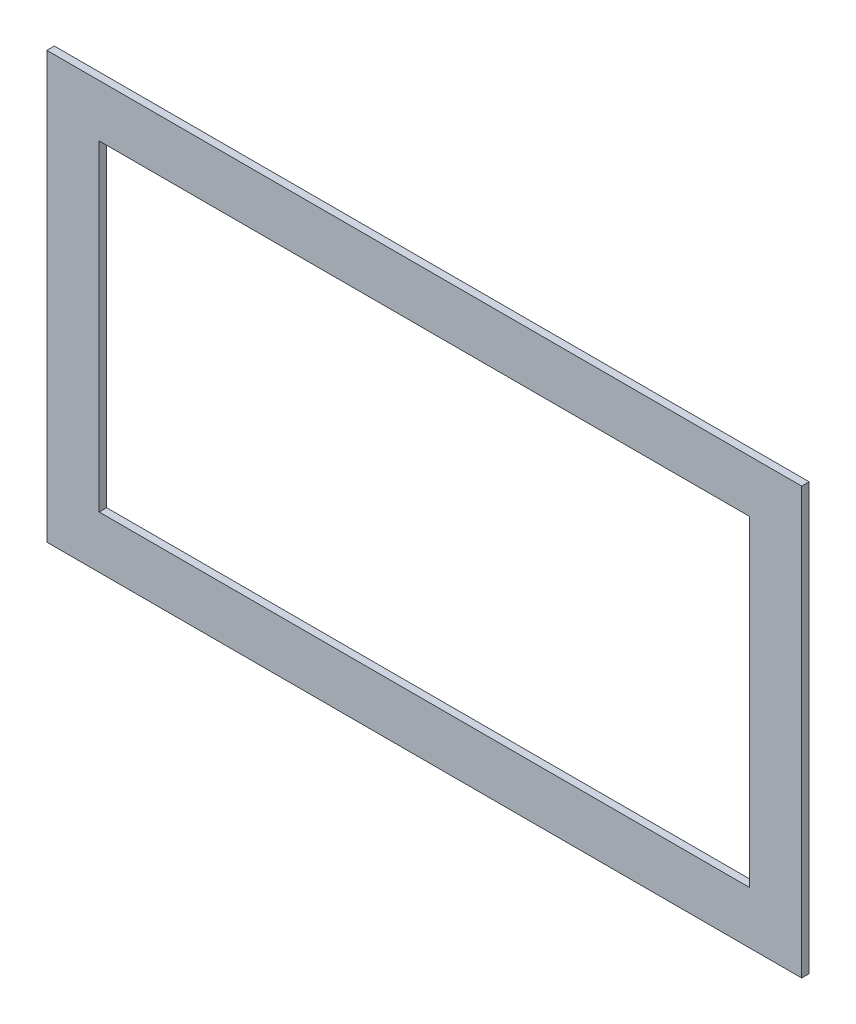
SolidWorks part; units mm, degrees
ref_plane "Front Plane" through (0, 0, 0) normal (0, 0, 1) x (1, 0, 0)
ref_plane "Top Plane" through (0, 0, 0) normal (0, 1, 0) x (1, 0, 0)
ref_plane "Right Plane" through (0, 0, 0) normal (1, 0, 0) x (0, 0, -1)
sketch "Sketch1" plane through (0, 0, 0) normal (0, 0, 1) x (1, 0, 0)
  line L1 (0, 0) -> (101, 0)
  line L2 (0, 0) -> (0, 57)
  line L3 (0, 57) -> (101, 57)
  line L4 (101, 0) -> (101, 57)
  line L5 (7, 7) -> (94, 7)
  line L6 (7, 7) -> (7, 50)
  line L7 (7, 50) -> (94, 50)
  line L8 (94, 7) -> (94, 50)
  dimension "D1" = 7
  dimension "D2" = 94
  dimension "D3" = 101
  dimension "D4" = 7
  dimension "D5" = 50
  dimension "D6" = 57
extrude "Profile" add sketch "Sketch1" along normal blind 1
equation "\"Profile_Depth\"= 1mm"
equation "\"D1@Profile\" = \"Profile_Depth\""
equation "\"Profile_Sketch_1\"= 7mm"
equation "\"D1@Sketch1\" = \"Profile_Sketch_1\""
equation "\"Profile_Sketch_2\"= 94mm"
equation "\"D2@Sketch1\" = \"Profile_Sketch_2\""
equation "\"Profile_Sketch_3\"= 101mm"
equation "\"D3@Sketch1\" = \"Profile_Sketch_3\""
equation "\"Profile_Sketch_4\"= 7mm"
equation "\"D4@Sketch1\" = \"Profile_Sketch_4\""
equation "\"Profile_Sketch_5\"= 50mm"
equation "\"D5@Sketch1\" = \"Profile_Sketch_5\""
equation "\"Profile_Sketch_6\"= 57mm"
equation "\"D6@Sketch1\" = \"Profile_Sketch_6\""
equation "\"EnvelopeWidth\"= 101mm"
equation "\"EnvelopeHeight\"= 57mm"
